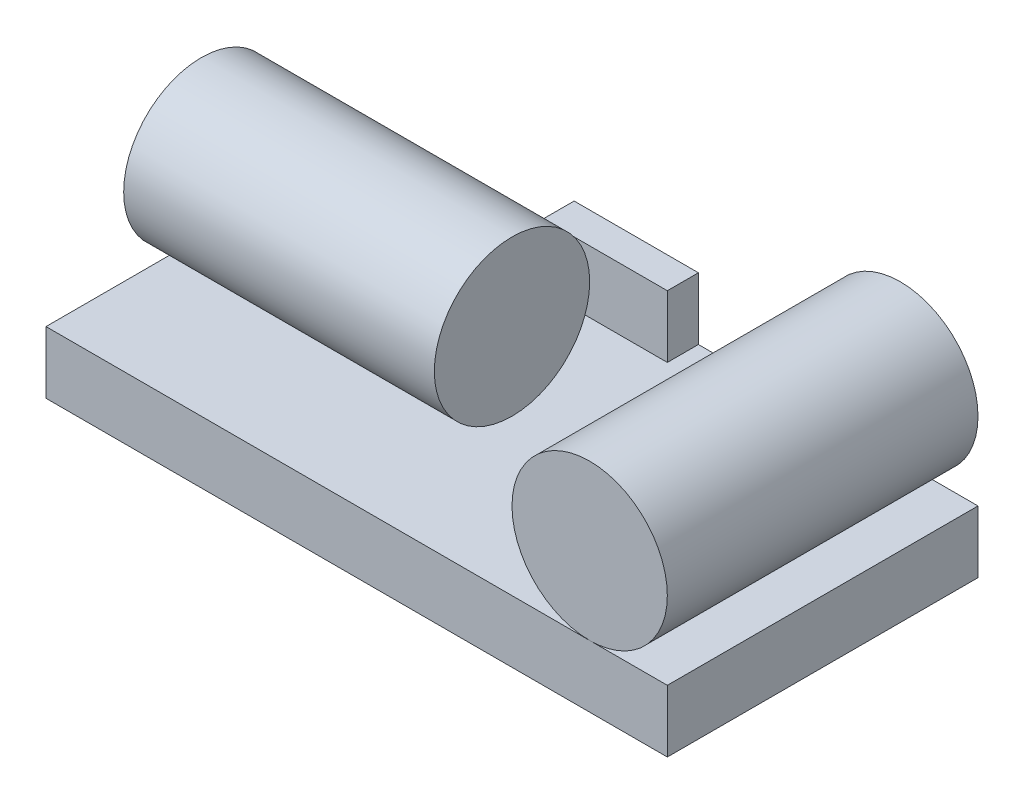
SolidWorks part; units mm, degrees
ref_plane "前视基准面" through (0, 0, 0) normal (0, 0, 1) x (1, 0, 0)
ref_plane "上视基准面" through (0, 0, 0) normal (0, 1, 0) x (1, 0, 0)
ref_plane "右视基准面" through (0, 0, 0) normal (1, 0, 0) x (0, 0, -1)
other "Configuration Table"
sketch "草图1" plane through (0, 0, 0) normal (0, 1, 0) x (1, 0, 0)
  line L1 (0, 0) -> (20, 0)
  line L2 (0, 0) -> (0, 10)
  line L3 (0, 10) -> (20, 10)
  line L4 (20, 0) -> (20, 10)
  dimension "D1" = 20
  dimension "D2" = 10
extrude "凸台-拉伸1" add sketch "草图1" along normal blind 2
sketch "草图2" plane through (0, 0, 0) normal (0, 0, 1) x (1, 0, 0)
  line L0 (0, 2) -> (20, 2) construction
  line L1 (20, 2) -> (20, 0) construction
  circle A0 centre (17.5, 4.5) radius 2.5
  dimension "D1" = 5
extrude "凸台-拉伸2" add sketch "草图2" against normal up to surface (10 mm away) separate body up to face at (10, 1, -10)
sketch "草图3" plane through (0, 0, 0) normal (-1, 0, 0) x (0, 0, 1)
  line L0 (-10, 2) -> (0, 2) construction
  circle A0 centre (-5, 4.5) radius 2.5
  point P4 (-5, 2)
  dimension "D1" = 5
extrude "凸台-拉伸3" add sketch "草图3" against normal blind 10 separate body
sketch "草图4" plane through (0, 2, 0) normal (0, 1, 0) x (1, 0, 0)
  line L0 (20, 10) -> (0, 10) construction
  line L1 (7, 10) -> (11, 10)
  line L2 (7, 10) -> (7, 9)
  line L3 (7, 9) -> (11, 9)
  line L4 (11, 10) -> (11, 9)
  line L5 (0, 10) -> (0, 0) construction
  dimension "D1" = 1
  dimension "D2" = 4
  dimension "D3" = 7
extrude "凸台-拉伸4" add sketch "草图4" along normal blind 2
